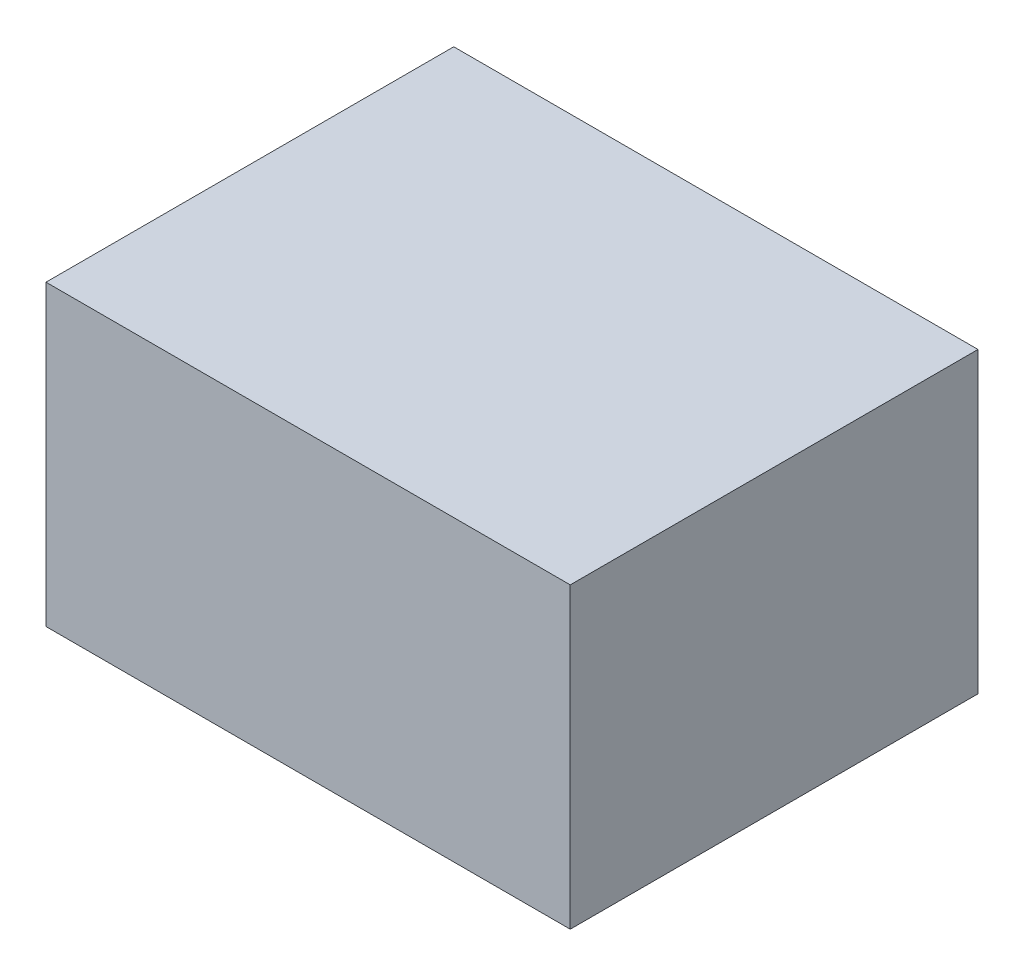
SolidWorks part; units mm, degrees
ref_plane "前基準面" through (0, 0, 0) normal (0, 0, 1) x (1, 0, 0)
ref_plane "上基準面" through (0, 0, 0) normal (0, 1, 0) x (1, 0, 0)
ref_plane "右基準面" through (0, 0, 0) normal (1, 0, 0) x (0, 0, -1)
sketch "草圖1" plane through (0, 0, 0) normal (0, 0, 1) x (1, 0, 0)
  line L0 (-2.25, -1.21) -> (2.25, -1.21)
  line L1 (2.25, -1.21) -> (2.25, 1.35)
  line L2 (2.25, 1.35) -> (-2.25, 1.35)
  line L3 (-2.25, 1.35) -> (-2.25, -1.21)
extrude "body" add sketch "草圖1" along normal blind 3.5
sketch "草圖2" plane through (0, 0, 0) normal (0, 0, 1) x (1, 0, 0)
  line L0 (-1, -2.04) -> (1, -2.04)
  line L1 (1, -2.04) -> (1, -1.21)
  line L2 (1, -1.21) -> (-1, -1.21)
  line L3 (-1, -1.21) -> (-1, -2.04)
extrude "stem full" add sketch "草圖2" along normal blind 2.55
sketch "草圖3" plane through (0, 0, 0) normal (0, 0, 1) x (1, 0, 0)
  line L0 (-1.2, -2.2) -> (1.2, -2.2)
  line L1 (1.2, -2.2) -> (1.2, -1.1)
  line L2 (1.2, -1.1) -> (-1.2, -1.1)
  line L3 (-1.2, -1.1) -> (-1.2, -2.2)
extrude "stem lower gap" cut sketch "草圖3" along normal blind 0.95
